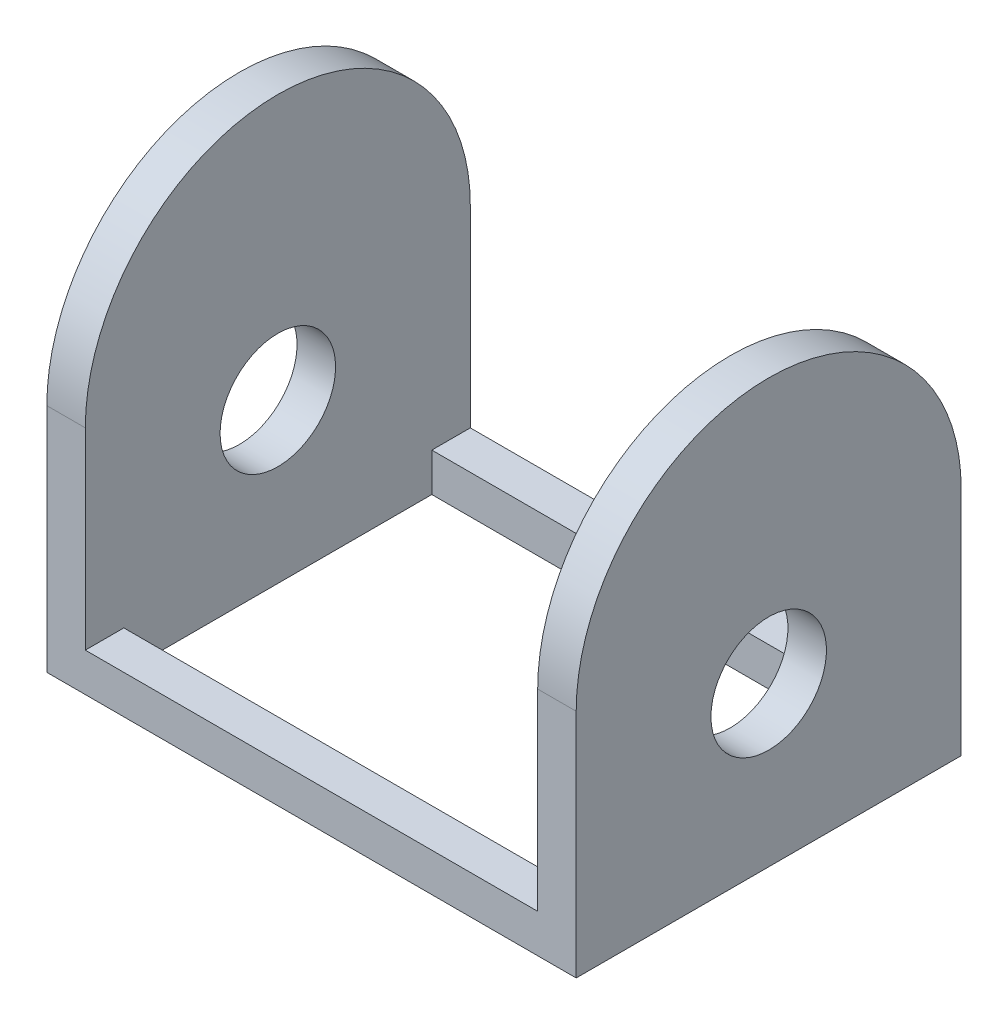
SolidWorks part; units mm, degrees
ref_plane "Front Plane" through (0, 0, 0) normal (0, 0, 1) x (1, 0, 0)
ref_plane "Top Plane" through (0, 0, 0) normal (0, 1, 0) x (1, 0, 0)
ref_plane "Right Plane" through (0, 0, 0) normal (1, 0, 0) x (0, 0, -1)
sketch "Sketch1" plane through (0, 0, 0) normal (0, 1, 0) x (1, 0, 0)
  line L0 (-44.7919, 0) -> (31.1193, 0) construction
  line L6 (-27.5, 20) -> (0, 20)
  line L7 (-27.5, 20) -> (-27.5, -20)
  line L8 (-27.5, -20) -> (0, -20)
  line L9 (0, 20) -> (0, -20)
  point P8 (-44.7919, 0)
  dimension "D1" = 27.5
  dimension "D2" = 40
extrude "Boss-Extrude4" add sketch "Sketch1" along normal blind 4
sketch "Sketch5" plane through (0, 4, 0) normal (0, 1, 0) x (1, 0, 0)
  line L0 (-27.5, -20) -> (0, -20) construction
  line L1 (-27.5, 20) -> (-23.5, 20)
  line L2 (-27.5, 20) -> (-27.5, -20)
  line L3 (-27.5, -20) -> (-23.5, -20)
  line L4 (-23.5, 20) -> (-23.5, -20)
  dimension "D1" = 4
extrude "Boss-Extrude5" add sketch "Sketch5" along normal blind 20
sketch "Sketch6" plane through (-27.5, 0, 0) normal (-1, 0, 0) x (0, 0, 1)
  line L0 (0, 0) -> (0, 4) construction
  line L1 (0, 4) -> (0, 16.5) construction
  circle A0 centre (0, 16.5) radius 6
  dimension "D3" = 12
  dimension "D1" = 4
  dimension "D2" = 12.5
extrude "Cut-Extrude2" cut sketch "Sketch6" against normal through all
sketch "Sketch7" plane through (-27.5, 0, 0) normal (-1, 0, 0) x (0, 0, 1)
  line L0 (-20, 24) -> (20, 24) construction
  line L2 (-20, 24) -> (20, 24)
  arc A0 (-20, 24) -> (20, 24) centre (0, 24) cw
extrude "Boss-Extrude6" add sketch "Sketch7" against normal up to surface (4 mm away) up to face at (-23.5, 16.5, 6)
mirror "Mirror2" about plane through (0, 0, 0) normal (1, 0, 0) of "Boss-Extrude4", "Boss-Extrude5", "Cut-Extrude2", "Boss-Extrude6"
sketch "Sketch8" plane through (0, 4, 0) normal (0, 1, 0) x (1, 0, 0)
  line L1 (-23.5, 16) -> (23.5, 16)
  line L2 (-23.5, 16) -> (-23.5, -16)
  line L3 (-23.5, -16) -> (23.5, -16)
  line L4 (23.5, 16) -> (23.5, -16)
  line L5 (-23.5, 16) -> (23.5, -16) construction
  line L6 (-23.5, -16) -> (23.5, 16) construction
  line L10 (23.5, -20) -> (23.5, 20)
  line L11 (23.5, 20) -> (-23.5, 20)
  line L12 (-23.5, 20) -> (-23.5, -20)
  line L13 (-23.5, -20) -> (23.5, -20)
  line L14 (23.5, -20) -> (23.5, 20)
  line L15 (23.5, 20) -> (-23.5, 20)
  line L16 (-23.5, 20) -> (-23.5, -20)
  line L17 (-23.5, -20) -> (23.5, -20)
  point P0 (0, 0)
  dimension "D3" = 4
  dimension "D1" = 0
extrude "Cut-Extrude3" cut sketch "Sketch8" against normal through all contours L4 L1 L2 L3
